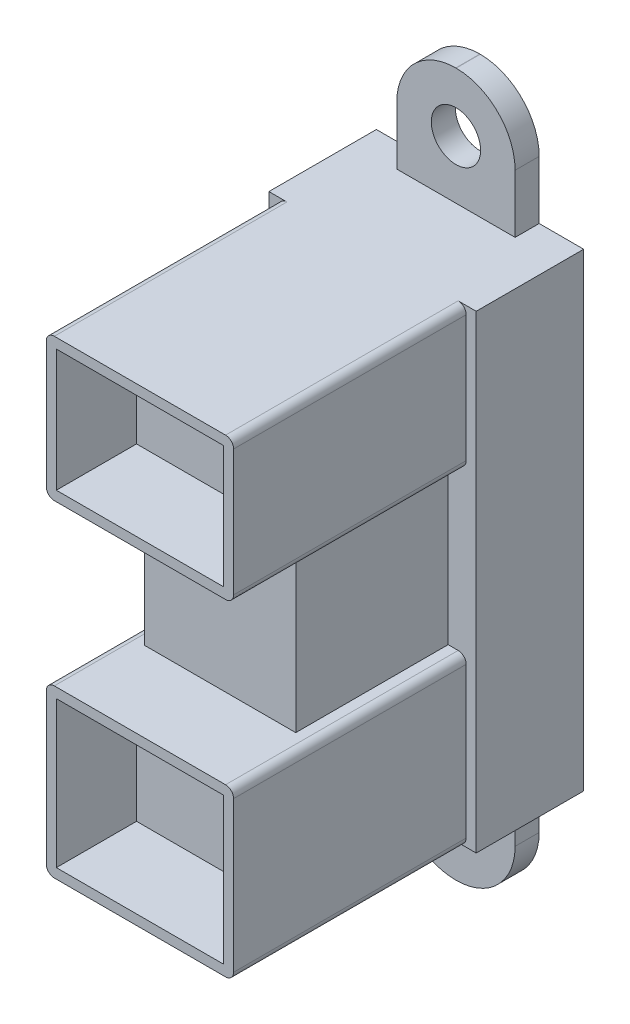
SolidWorks part; units mm, degrees
ref_plane "Front" through (0, 0, 0) normal (0, 0, 1) x (1, 0, 0)
ref_plane "Top" through (0, 0, 0) normal (0, 1, 0) x (1, 0, 0)
ref_plane "Right" through (0, 0, 0) normal (1, 0, 0) x (0, 0, -1)
sketch "Sketch1" plane through (0, 0, 0) normal (0, 0, 1) x (1, 0, 0)
  line L1 (0, 0) -> (13.1318, 0)
  line L2 (0, 0) -> (0, 29.718)
  line L3 (0, 29.718) -> (13.1318, 29.718)
  line L4 (13.1318, 0) -> (13.1318, 29.718)
  dimension "D1" = 13.1318
  dimension "D2" = 29.718
extrude "Extrude1" add sketch "Sketch1" along normal blind 21.5392
sketch "Sketch2" plane through (0, 0, 21.5392) normal (0, 0, 1) x (1, 0, 0)
  line L0 (0.635, 29.718) -> (0.635, 0)
  line L1 (13.1318, 29.718) -> (0, 29.718) construction
  line L2 (0, 0) -> (13.1318, 0) construction
  line L3 (6.5659, 29.718) -> (6.5659, 19.8573) construction
  line L4 (0, 29.718) -> (0, 0) construction
  line L5 (0.635, 29.718) -> (0, 29.718)
  line L6 (0, 29.718) -> (0, 0)
  line L7 (0, 0) -> (0.635, 0)
  line L8 (13.1318, 0) -> (12.4968, 0)
  line L9 (13.1318, 29.718) -> (13.1318, 0)
  line L10 (12.4968, 29.718) -> (13.1318, 29.718)
  line L11 (12.4968, 29.718) -> (12.4968, 0)
  dimension "D1" = 0.635
extrude "Cut-Extrude1" cut sketch "Sketch2" against normal blind 14.732
sketch "Sketch3" plane through (0, 0, 21.5392) normal (0, 0, 1) x (1, 0, 0)
  line L0 (12.4968, 29.718) -> (12.4968, 0) construction
  line L3 (0.635, 20.701) -> (12.4968, 20.701)
  line L5 (0.635, 0) -> (0.635, 29.718) construction
  line L6 (0.635, 10.541) -> (12.4968, 10.541)
  line L10 (0.635, 20.701) -> (0.635, 10.541)
  line L11 (12.4968, 20.701) -> (12.4968, 10.541)
extrude "Cut-Extrude2" cut sketch "Sketch3" against normal blind 5.08
sketch "Sketch5" plane through (0, 0, 6.8072) normal (0, 0, 1) x (1, 0, 0)
  line L0 (0, 29.718) -> (0, 0) construction
  line L1 (0, 20.701) -> (1.778, 20.701)
  line L2 (0, 20.701) -> (0, 10.541)
  line L3 (0, 10.541) -> (1.778, 10.541)
  line L4 (1.778, 20.701) -> (1.778, 10.541)
  line L5 (0.635, 10.541) -> (12.4968, 10.541) construction
  line L6 (6.5659, 20.701) -> (6.5659, 14.4921) construction
  line L7 (12.4968, 20.701) -> (0.635, 20.701) construction
  line L8 (13.1318, 10.541) -> (11.3538, 10.541)
  line L9 (13.1318, 20.701) -> (13.1318, 10.541)
  line L10 (11.3538, 20.701) -> (11.3538, 10.541)
  line L11 (13.1318, 20.701) -> (11.3538, 20.701)
  dimension "D1" = 1.778
extrude "Cut-Extrude3" cut sketch "Sketch5" along normal through all
fillet "Fillet1" radius 0.508 8 edges at (0.635, 10.541, 14.1732) (0.635, 0, 14.1732) (12.4968, 0, 14.1732) (12.4968, 10.541, 14.1732) (12.4968, 29.718, 14.1732) (12.4968, 20.701, 14.1732) (0.635, 20.701, 14.1732) (0.635, 29.718, 14.1732)
sketch "Sketch7" plane through (0, 0, 0) normal (0, 0, -1) x (-1, 0, 0)
  line L0 (-13.1318, 29.718) -> (0, 29.718) construction
  line L1 (-10.3124, 29.718) -> (-2.8194, 29.718)
  line L2 (-10.3124, 29.718) -> (-10.3124, 37.1348)
  line L3 (-10.3124, 37.1348) -> (-2.8194, 37.1348)
  line L4 (-2.8194, 29.718) -> (-2.8194, 37.1348)
  line L5 (-13.1318, 14.859) -> (0, 14.859) construction
  line L6 (-13.1318, 0) -> (-13.1318, 29.718) construction
  line L7 (0, 29.718) -> (0, 0) construction
  line L8 (-10.3124, 0) -> (-2.8194, 0)
  line L9 (-2.8194, 0) -> (-2.8194, -7.4168)
  line L10 (-10.3124, 0) -> (-10.3124, -7.4168)
  line L11 (-10.3124, -7.4168) -> (-2.8194, -7.4168)
  point P6 (-6.5659, 29.718)
  point P7 (-6.5659, 29.718)
  dimension "D1" = 7.493
  dimension "D2" = 7.4168
extrude "Extrude4" add sketch "Sketch7" against normal blind 1.524
fillet "Fillet3" radius 3.7338 4 edges at (10.3124, -7.4168, 0.762) (2.8194, -7.4168, 0.762) (2.8194, 37.1348, 0.762) (10.3124, 37.1348, 0.762)
sketch "Sketch9" plane through (0, 0, 0) normal (0, 0, -1) x (-1, 0, 0)
  line L0 (-10.3124, 33.401) -> (-2.8194, 33.401) construction
  line L1 (-6.5659, 33.401) -> (-6.5532, 37.1348) construction
  line L2 (-13.1318, 14.859) -> (0, 14.859) construction
  line L3 (-13.1318, 0) -> (-13.1318, 29.718) construction
  line L4 (0, 29.718) -> (0, 0) construction
  circle A0 centre (-6.5659, 33.401) radius 1.5621
  circle A1 centre (-6.5659, -3.683) radius 1.5621
  dimension "D1" = 3.1242
extrude "Cut-Extrude4" cut sketch "Sketch9" against normal blind 1.524
sketch "Sketch11" plane through (0, 0, 21.5392) normal (0, 0, 1) x (1, 0, 0)
  line L8 (11.8618, 21.336) -> (11.8618, 29.083)
  line L9 (11.8618, 29.083) -> (1.27, 29.083)
  line L10 (1.27, 29.083) -> (1.27, 21.336)
  line L11 (1.27, 21.336) -> (11.8618, 21.336)
  line L12 (11.8618, 21.336) -> (11.8618, 29.083)
  line L13 (11.8618, 29.083) -> (1.27, 29.083)
  line L14 (1.27, 29.083) -> (1.27, 21.336)
  line L15 (1.27, 21.336) -> (11.8618, 21.336)
  dimension "D1" = 0.635
extrude "Cut-Extrude5" cut sketch "Sketch11" against normal blind 5.08
sketch "Sketch12" plane through (0, 0, 21.5392) normal (0, 0, 1) x (1, 0, 0)
  line L8 (11.8618, 9.906) -> (1.27, 9.906)
  line L9 (1.27, 9.906) -> (1.27, 0.635)
  line L10 (1.27, 0.635) -> (11.8618, 0.635)
  line L11 (11.8618, 0.635) -> (11.8618, 9.906)
  line L12 (11.8618, 9.906) -> (1.27, 9.906)
  line L13 (1.27, 9.906) -> (1.27, 0.635)
  line L14 (1.27, 0.635) -> (11.8618, 0.635)
  line L15 (11.8618, 0.635) -> (11.8618, 9.906)
  dimension "D1" = 0.635
extrude "Cut-Extrude6" cut sketch "Sketch12" against normal blind 5.08
sketch "Sketch13" plane through (0, 0, 0) normal (-1, 0, 0) x (0, 0, 1)
  line L0 (0, 29.718) -> (0, 0) construction
  line L1 (0, 18.669) -> (9.271, 18.669)
  line L2 (0, 18.669) -> (0, 11.049)
  line L3 (0, 11.049) -> (9.271, 11.049)
  line L4 (9.271, 18.669) -> (9.271, 11.049)
  point P6 (0, 14.859)
  point P7 (0, 14.859)
  dimension "D1" = 7.62
  dimension "D2" = 9.271
extrude "Extrude5" add sketch "Sketch13" along normal blind 6.35
chamfer "Chamfer1" distance 1.27 angle 45 1 edges at (0, 14.859, 9.271)
sketch "Sketch14" plane through (0, 0, 0) normal (0, 0, -1) x (-1, 0, 0)
  line L1 (0, 18.669) -> (6.35, 18.669)
  line L2 (0, 18.669) -> (0, 11.049)
  line L3 (0, 11.049) -> (6.35, 11.049)
  line L4 (6.35, 18.669) -> (6.35, 11.049)
extrude "Cut-Extrude7" cut sketch "Sketch14" against normal blind 3.048
sketch "Sketch15" plane through (-6.35, 0, 0) normal (-1, 0, 0) x (0, 0, 1)
  line L0 (7.7607, 18.669) -> (7.7607, 11.049) construction
  line L1 (9.271, 18.669) -> (3.048, 18.669) construction
  line L2 (3.048, 11.049) -> (9.271, 11.049) construction
  line L19 (2.54, 21.209) -> (4.2672, 21.209)
  line L20 (4.2672, 21.209) -> (4.2672, 27.178)
  line L21 (4.2672, 27.178) -> (2.54, 27.178)
  line L22 (2.54, 27.178) -> (2.54, 21.209)
  line L23 (2.54, 21.209) -> (4.2672, 21.209)
  line L24 (4.2672, 21.209) -> (4.2672, 27.178)
  line L25 (4.2672, 27.178) -> (2.54, 27.178)
  line L26 (2.54, 27.178) -> (2.54, 21.209)
  line L27 (9.017, 18.415) -> (3.302, 18.415)
  line L28 (3.302, 18.415) -> (3.302, 11.303)
  line L29 (3.302, 11.303) -> (9.017, 11.303)
  line L30 (9.017, 11.303) -> (9.017, 18.415)
  line L31 (9.017, 18.415) -> (3.302, 18.415)
  line L32 (3.302, 18.415) -> (3.302, 11.303)
  line L33 (3.302, 11.303) -> (9.017, 11.303)
  line L34 (9.017, 11.303) -> (9.017, 18.415)
  circle A0 centre (7.7607, 14.859) radius 0.127
  circle A1 centre (7.7607, 17.399) radius 0.127
  circle A2 centre (7.7607, 12.319) radius 0.127
  dimension "D1" = 2.54
  dimension "D2" = 2.54
  dimension "D3" = 0.254
  dimension "D4" = 0.254
  dimension "D5" = 0.254
  dimension "D6" = 2.54
  dimension "D7" = 0.254
extrude "Cut-Extrude8" cut sketch "Sketch15" against normal blind 5.08
